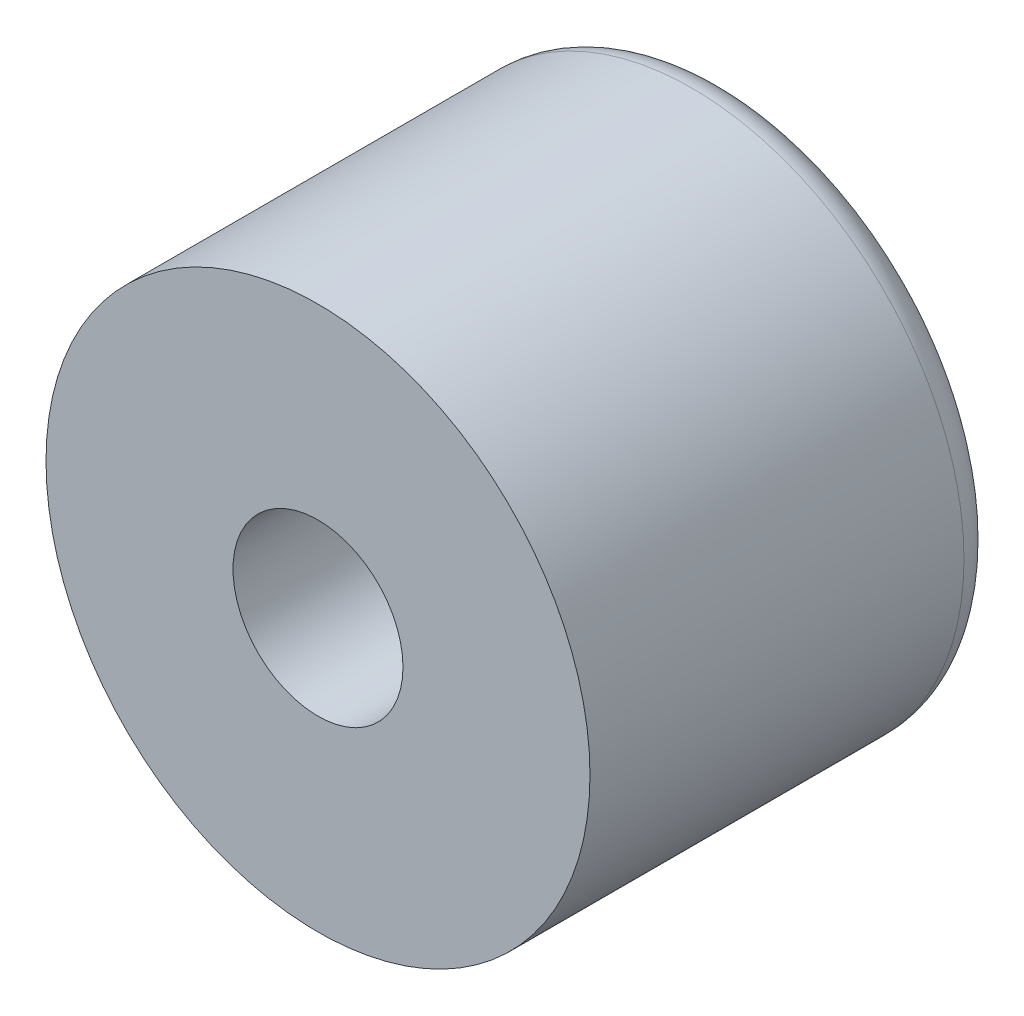
SolidWorks part; units mm, degrees
material "Gray Cast Iron"
ref_plane "Front Plane" through (0, 0, 0) normal (0, 0, 1) x (1, 0, 0)
ref_plane "Top Plane" through (0, 0, 0) normal (0, 1, 0) x (1, 0, 0)
ref_plane "Right Plane" through (0, 0, 0) normal (1, 0, 0) x (0, 0, -1)
sketch "Sketch1" plane through (0, 0, 0) normal (0, 0, 1) x (1, 0, 0)
  circle A0 centre (0, 0) radius 8
  dimension "D1" = 16
extrude "Boss-Extrude1" add sketch "Sketch1" along normal blind 12
sketch "Sketch2" plane through (0, 0, 12) normal (0, 0, 1) x (1, 0, 0)
  circle A0 centre (0, 0) radius 2.5
  dimension "D1" = 5
extrude "Cut-Extrude1" cut sketch "Sketch2" against normal blind 5
fillet "Fillet1" radius 1 1 edges at (8, 0, 0)
